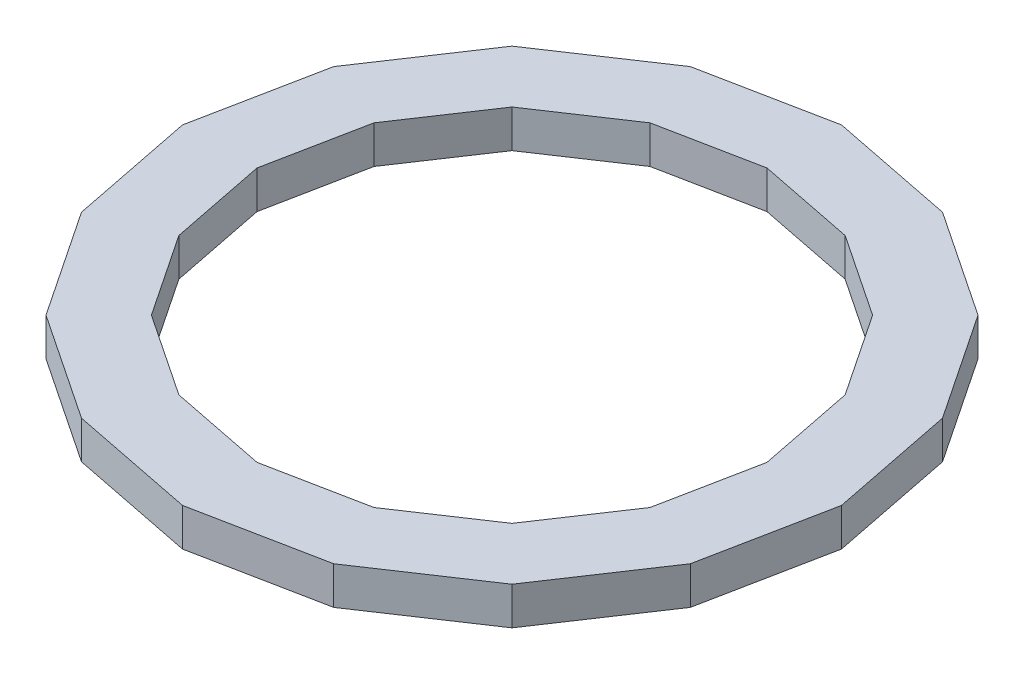
SolidWorks part; units mm, degrees
ref_plane "Front Plane" through (0, 0, 0) normal (0, 0, 1) x (1, 0, 0)
ref_plane "Top Plane" through (0, 0, 0) normal (0, 1, 0) x (1, 0, 0)
ref_plane "Right Plane" through (0, 0, 0) normal (1, 0, 0) x (0, 0, -1)
sketch "Sketch1" plane through (0, 0, 0) normal (0, 1, 0) x (1, 0, 0)
  line L1 (128.4485, 0) -> (118.6709, 49.1551)
  line L2 (118.6709, 49.1551) -> (90.8268, 90.8268)
  line L3 (90.8268, 90.8268) -> (49.1551, 118.6709)
  line L4 (49.1551, 118.6709) -> (0, 128.4485)
  line L5 (0, 128.4485) -> (-49.1551, 118.6709)
  line L6 (-49.1551, 118.6709) -> (-90.8268, 90.8268)
  line L7 (-90.8268, 90.8268) -> (-118.6709, 49.1551)
  line L8 (-118.6709, 49.1551) -> (-128.4485, 0)
  line L9 (-128.4485, 0) -> (-118.6709, -49.1551)
  line L10 (-118.6709, -49.1551) -> (-90.8268, -90.8268)
  line L11 (-90.8268, -90.8268) -> (-49.1551, -118.6709)
  line L12 (-49.1551, -118.6709) -> (0, -128.4485)
  line L13 (0, -128.4485) -> (49.1551, -118.6709)
  line L14 (49.1551, -118.6709) -> (90.8268, -90.8268)
  line L15 (90.8268, -90.8268) -> (118.6709, -49.1551)
  line L16 (118.6709, -49.1551) -> (128.4485, 0)
  line L17 (166, 0) -> (153.364, 63.5255)
  line L18 (153.364, 63.5255) -> (117.3797, 117.3797)
  line L19 (117.3797, 117.3797) -> (63.5255, 153.364)
  line L20 (63.5255, 153.364) -> (0, 166)
  line L21 (0, 166) -> (-63.5255, 153.364)
  line L22 (-63.5255, 153.364) -> (-117.3797, 117.3797)
  line L23 (-117.3797, 117.3797) -> (-153.364, 63.5255)
  line L24 (-153.364, 63.5255) -> (-166, 0)
  line L25 (-166, 0) -> (-153.364, -63.5255)
  line L26 (-153.364, -63.5255) -> (-117.3797, -117.3797)
  line L27 (-117.3797, -117.3797) -> (-63.5255, -153.364)
  line L28 (-63.5255, -153.364) -> (0, -166)
  line L29 (0, -166) -> (63.5255, -153.364)
  line L30 (63.5255, -153.364) -> (117.3797, -117.3797)
  line L31 (117.3797, -117.3797) -> (153.364, -63.5255)
  line L32 (153.364, -63.5255) -> (166, 0)
  circle A0 centre (0, 0) radius 125.9804 construction
  circle A1 centre (0, 0) radius 162.8104 construction
  dimension "D1" = 64.77
  dimension "D2" = 36.83
extrude "Boss-Extrude1" add sketch "Sketch1" along normal blind 19.05
